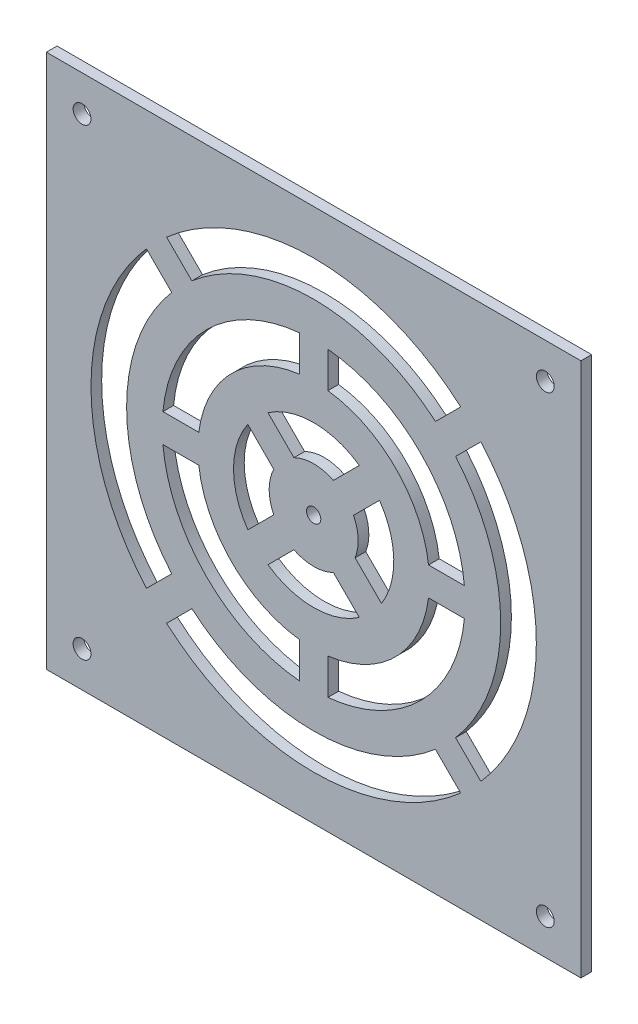
SolidWorks part; units mm, degrees
ref_plane "Front Plane" through (0, 0, 0) normal (0, 0, 1) x (1, 0, 0)
ref_plane "Top Plane" through (0, 0, 0) normal (0, 1, 0) x (1, 0, 0)
ref_plane "Right Plane" through (0, 0, 0) normal (1, 0, 0) x (0, 0, -1)
sketch "Sketch1" plane through (0, 0, 0) normal (0, 0, 1) x (1, 0, 0)
  line L1 (71.8966, -8.7931) -> (221.8966, -8.7931)
  line L2 (71.8966, -8.7931) -> (71.8966, 141.2069)
  line L3 (71.8966, 141.2069) -> (221.8966, 141.2069)
  line L4 (221.8966, -8.7931) -> (221.8966, 141.2069)
  line L5 (71.8966, -8.7931) -> (221.8966, 141.2069) construction
  line L6 (71.8966, 141.2069) -> (221.8966, -8.7931) construction
  dimension "D1" = 150
  dimension "D2" = 150
extrude "Boss-Extrude1" add sketch "Sketch1" along normal blind 3
sketch "Sketch2" plane through (0, 0, 3) normal (0, 0, 1) x (1, 0, 0)
  line L0 (99.9731, 107.4735) -> (107.0615, 100.3851)
  line L1 (146.8966, 141.2069) -> (146.8966, 128.6948) construction
  line L2 (221.8966, 141.2069) -> (71.8966, 141.2069) construction
  line L3 (146.8966, -8.7931) -> (146.8966, 3.719) construction
  line L4 (71.8966, -8.7931) -> (221.8966, -8.7931) construction
  line L5 (71.8966, 141.2069) -> (221.8966, -8.7931) construction
  line L6 (71.8966, -8.7931) -> (221.8966, 141.2069) construction
  line L7 (105.63, 113.1303) -> (112.7184, 106.0419)
  line L8 (109.1742, 109.5861) -> (106.3457, 106.7577) construction
  line L9 (106.3457, 106.7577) -> (103.5173, 103.9293) construction
  line L10 (187.4474, 25.6561) -> (184.6189, 22.8277) construction
  line L11 (190.2758, 28.4845) -> (187.4474, 25.6561) construction
  line L12 (193.82, 24.9403) -> (186.7316, 32.0287)
  line L13 (188.1631, 19.2835) -> (181.0747, 26.3719)
  line L14 (186.7316, 100.3851) -> (193.82, 107.4735)
  line L15 (181.0747, 106.0419) -> (188.1631, 113.1303)
  line L16 (184.6189, 109.5861) -> (187.4474, 106.7577) construction
  line L17 (187.4474, 106.7577) -> (190.2758, 103.9293) construction
  line L18 (106.3457, 25.6561) -> (109.1742, 22.8277) construction
  line L19 (103.5173, 28.4845) -> (106.3457, 25.6561) construction
  line L20 (112.7184, 26.3719) -> (105.63, 19.2835)
  line L21 (107.0615, 32.0287) -> (99.9731, 24.9403)
  line L22 (146.8966, 141.2069) -> (146.8966, -8.7931) construction
  line L23 (221.8966, 66.2069) -> (71.8966, 66.2069) construction
  line L24 (221.8966, -8.7931) -> (221.8966, 141.2069) construction
  line L25 (71.8966, 141.2069) -> (71.8966, -8.7931) construction
  line L26 (150.8966, 108.5061) -> (150.8966, 98.4476)
  line L27 (142.8966, 108.5061) -> (142.8966, 98.4476)
  line L28 (142.8966, 103.4769) -> (146.8966, 103.4769) construction
  line L29 (146.8966, 103.4769) -> (150.8966, 103.4769) construction
  line L30 (142.8966, 28.9369) -> (146.8966, 28.9369) construction
  line L31 (146.8966, 28.9369) -> (150.8966, 28.9369) construction
  line L32 (150.8966, 23.9077) -> (150.8966, 33.9662)
  line L33 (142.8966, 23.9077) -> (142.8966, 33.9662)
  line L34 (189.1957, 70.2069) -> (179.1373, 70.2069)
  line L35 (189.1957, 62.2069) -> (179.1373, 62.2069)
  line L36 (184.1665, 70.2069) -> (184.1665, 66.2069) construction
  line L37 (184.1665, 66.2069) -> (184.1665, 62.2069) construction
  line L38 (109.6266, 70.2069) -> (109.6266, 66.2069) construction
  line L39 (109.6266, 66.2069) -> (109.6266, 62.2069) construction
  line L40 (104.5974, 62.2069) -> (114.6558, 62.2069)
  line L41 (104.5974, 70.2069) -> (114.6558, 70.2069)
  line L42 (181.0747, 106.0419) -> (107.0615, 32.0287) construction
  line L43 (112.7184, 26.3719) -> (186.7316, 100.3851) construction
  line L44 (135.7031, 71.7435) -> (128.4204, 79.0262)
  line L45 (107.0615, 100.3851) -> (181.0747, 26.3719) construction
  line L46 (152.4332, 77.4004) -> (159.7159, 84.6831)
  line L47 (165.3728, 79.0262) -> (158.09, 71.7435)
  line L48 (141.3599, 55.0134) -> (134.0772, 47.7307)
  line L49 (135.7031, 60.6703) -> (128.4204, 53.3875)
  line L50 (158.5217, 61.6459) -> (165.9328, 54.2349)
  line L51 (159.7159, 47.7307) -> (152.4332, 55.0134)
  line L52 (134.0772, 84.6831) -> (141.3599, 77.4004)
  circle A1 centre (146.8966, 66.2069) radius 62.4879
  circle A2 centre (146.8966, 66.2069) radius 52.4879
  circle A3 centre (146.8966, 66.2069) radius 42.4879
  circle A4 centre (146.8966, 66.2069) radius 32.4879
  circle A5 centre (146.8966, 66.2069) radius 22.4879
  circle A6 centre (146.8966, 66.2069) radius 12.4879
  dimension "D1" = 10
  dimension "D3" = 10
  dimension "D7" = 10
  dimension "D9" = 10
  dimension "D10" = 10
  dimension "D4" = 8
  dimension "D5" = 8
  dimension "D6" = 8
  dimension "D8" = 8
  dimension "D11" = 8
extrude "Cut-Extrude1" cut sketch "Sketch2" against normal through all contours A2 L15 A1 L7 | A2 L0 A1 L21 | A2 L12 A1 L14 | A2 L20 A1 L13 | A4 L32 A3 L35 | A4 L40 A3 L33 | A4 L27 A3 L41 | A4 L34 A3 L26 | A6 L50 A5 L47 | A6 L46 A5 L52 | A6 L44 A5 L49 | A6 L48 A5 L51
sketch "Sketch4" plane through (0, 0, 3) normal (0, 0, 1) x (1, 0, 0)
  line L0 (81.8966, 141.2069) -> (81.8966, 131.2069) construction
  line L1 (221.8966, 141.2069) -> (71.8966, 141.2069) construction
  line L2 (81.8966, 131.2069) -> (71.8966, 131.2069) construction
  line L3 (71.8966, 141.2069) -> (71.8966, -8.7931) construction
  circle A1 centre (81.8966, 131.2069) radius 2.5
  circle A2 centre (211.8966, 131.2069) radius 2.5
  circle A3 centre (211.8966, 1.2069) radius 2.5
  circle A4 centre (81.8966, 1.2069) radius 2.5
  point P17 (146.8966, 66.2069)
  dimension "D2" = 5
  dimension "D1" = 10
  dimension "D3" = 4
extrude "Cut-Extrude2" cut sketch "Sketch4" against normal blind 3
sketch "Sketch5" plane through (0, 0, 3) normal (0, 0, 1) x (1, 0, 0)
  circle A0 centre (146.8966, 66.2069) radius 2
extrude "Cut-Extrude3" cut sketch "Sketch5" against normal blind 10
